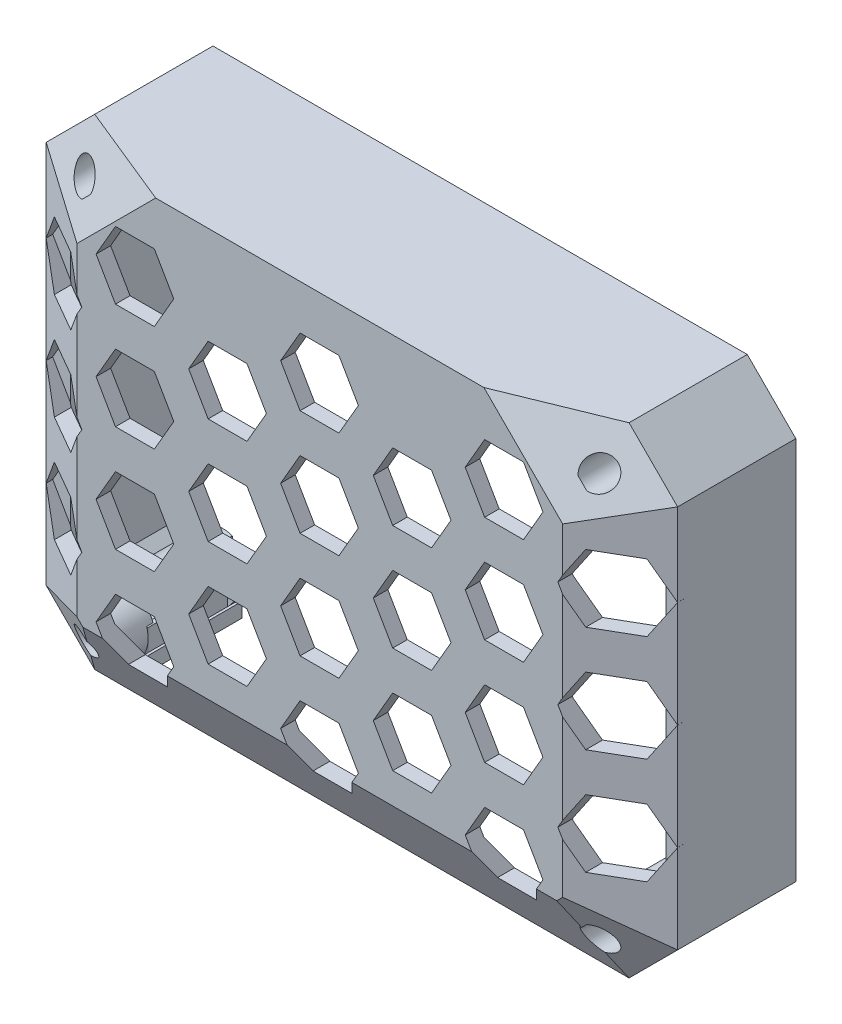
SolidWorks part; units mm, degrees
ref_plane "Front Plane" through (0, 0, 0) normal (0, 0, 1) x (1, 0, 0)
ref_plane "Top Plane" through (0, 0, 0) normal (0, 1, 0) x (1, 0, 0)
ref_plane "Right Plane" through (0, 0, 0) normal (1, 0, 0) x (0, 0, -1)
sketch "Sketch1" plane through (0, 0, 0) normal (0, 0, 1) x (1, 0, 0)
  line L10 (61.5236, 72) -> (30.4764, 72)
  line L11 (20.6915, 72) -> (-9, 72)
  line L12 (-9, 72) -> (-19, 62)
  line L13 (-19, 62) -> (-19, -17)
  line L14 (-19, -17) -> (-9, -27)
  line L15 (-9, -27) -> (101, -27)
  line L16 (101, -27) -> (111, -17)
  line L17 (111, -17) -> (111, 62)
  line L18 (111, 62) -> (101, 72)
  line L19 (101, 72) -> (71.3085, 72)
  line L22 (-9, 72) -> (-19, 62)
  line L23 (-19, 62) -> (-19, -17)
  line L24 (-19, -17) -> (-9, -27)
  line L25 (-9, -27) -> (101, -27)
  line L26 (101, -27) -> (111, -17)
  line L27 (111, -17) -> (111, 62)
  line L28 (111, 62) -> (101, 72)
  line L29 (101, 72) -> (-9, 72)
  arc A2 (61.5236, 72) -> (71.3085, 72) centre (66.4161, 73.0315) ccw
  arc A3 (20.6915, 72) -> (30.4764, 72) centre (25.5839, 73.0315) ccw
  dimension "D1" = 0
extrude "Extrude1" add sketch "Sketch1" along normal blind 33
chamfer "Chamfer1" distance 15 angle 30 8 edges at (-14, -22, 33) (-19, 22.5, 33) (-14, 67, 33) (46, 72, 33) (106, 67, 33) (46, -27, 33) (106, -22, 33) (111, 22.5, 33)
sketch "Sketch2" plane through (0, 0, 0) normal (0, 0, -1) x (-1, 0, 0)
  circle A0 centre (-99, 64) radius 3
  circle A1 centre (7, 64) radius 3
  circle A2 centre (7, -19) radius 3
  circle A3 centre (-99, -19) radius 3
  dimension "D1" = 6
extrude "Cut-Extrude1" cut sketch "Sketch2" against normal blind 30
shell "Shell1" thickness 3
sketch "Sketch3" plane through (0, 0, 33) normal (0, 0, 1) x (1, 0, 0)
  line L0 (3.932, 27.0855) -> (3.932, 19.0855) construction
  line L3 (15.932, 34.0137) -> (11.932, 40.9419)
  line L4 (11.932, 40.9419) -> (3.932, 40.9419)
  line L5 (3.932, 40.9419) -> (-0.068, 34.0137)
  line L6 (-0.068, 34.0137) -> (3.932, 27.0855)
  line L7 (3.932, 27.0855) -> (11.932, 27.0855)
  line L9 (-2.9962, 23.0855) -> (-6.9962, 30.0137)
  line L10 (-6.9962, 30.0137) -> (-14.9962, 30.0137)
  line L11 (-14.9962, 30.0137) -> (-18.9962, 23.0855)
  line L12 (-18.9962, 23.0855) -> (-14.9962, 16.1573)
  line L13 (-14.9962, 16.1573) -> (-6.9962, 16.1573)
  line L14 (-6.9962, 16.1573) -> (-2.9962, 23.0855)
  line L15 (15.932, 12.1573) -> (11.932, 19.0855)
  line L16 (11.932, 19.0855) -> (3.932, 19.0855)
  line L17 (3.932, 19.0855) -> (-0.068, 12.1573)
  line L18 (-0.068, 12.1573) -> (3.932, 5.2291)
  line L19 (3.932, 5.2291) -> (11.932, 5.2291)
  line L20 (11.932, 5.2291) -> (15.932, 12.1573)
  line L21 (11.932, 62.7983) -> (15.932, 55.8701)
  line L22 (-2.9962, 1.2291) -> (-6.9962, 8.1573)
  line L23 (-6.9962, 8.1573) -> (-14.9962, 8.1573)
  line L24 (-14.9962, 8.1573) -> (-18.9962, 1.2291)
  line L25 (-18.9962, 1.2291) -> (-14.9962, -5.6991)
  line L26 (-14.9962, -5.6991) -> (-6.9962, -5.6991)
  line L27 (-6.9962, -5.6991) -> (-2.9962, 1.2291)
  line L28 (15.932, -9.6991) -> (11.932, -2.7709)
  line L29 (11.932, -2.7709) -> (3.932, -2.7709)
  line L30 (3.932, -2.7709) -> (-0.068, -9.6991)
  line L31 (-0.068, -9.6991) -> (3.932, -16.6273)
  line L32 (3.932, -16.6273) -> (11.932, -16.6273)
  line L33 (11.932, -16.6273) -> (15.932, -9.6991)
  line L35 (15.932, 34.0137) -> (11.932, 27.0855)
  line L63 (53.932, 34.0137) -> (49.932, 40.9419)
  line L94 (49.932, 40.9419) -> (41.932, 40.9419)
  line L131 (41.932, 40.9419) -> (37.932, 34.0137)
  line L147 (11.932, 62.7983) -> (3.932, 62.7983)
  line L148 (3.932, 62.7983) -> (-0.068, 55.8701)
  line L149 (-0.068, 55.8701) -> (3.932, 48.9419)
  line L150 (3.932, 48.9419) -> (11.932, 48.9419)
  line L151 (11.932, 48.9419) -> (15.932, 55.8701)
  line L152 (-2.9962, 44.9419) -> (-6.9962, 51.8701)
  line L153 (-6.9962, 51.8701) -> (-14.9962, 51.8701)
  line L154 (-14.9962, 51.8701) -> (-18.9962, 44.9419)
  line L155 (-18.9962, 44.9419) -> (-14.9962, 38.0137)
  line L156 (-14.9962, 38.0137) -> (-6.9962, 38.0137)
  line L157 (-6.9962, 38.0137) -> (-2.9962, 44.9419)
  line L186 (3.932, 48.9419) -> (3.932, 40.9419) construction
  line L242 (37.932, 34.0137) -> (41.932, 27.0855)
  line L243 (41.932, 27.0855) -> (49.932, 27.0855)
  line L244 (35.0038, 23.0855) -> (31.0038, 30.0137)
  line L245 (31.0038, 30.0137) -> (23.0038, 30.0137)
  line L246 (23.0038, 30.0137) -> (19.0038, 23.0855)
  line L247 (19.0038, 23.0855) -> (23.0038, 16.1573)
  line L248 (23.0038, 16.1573) -> (31.0038, 16.1573)
  line L249 (31.0038, 16.1573) -> (35.0038, 23.0855)
  line L250 (53.932, 12.1573) -> (49.932, 19.0855)
  line L262 (49.932, 19.0855) -> (41.932, 19.0855)
  line L263 (41.932, 19.0855) -> (37.932, 12.1573)
  line L279 (37.932, 12.1573) -> (41.932, 5.2291)
  line L299 (17.0432, 35.9383) -> (21.0432, 42.8665) [skipped]
  line L303 (41.932, 5.2291) -> (49.932, 5.2291)
  line L304 (49.932, 5.2291) -> (53.932, 12.1573)
  line L316 (49.932, 62.7983) -> (53.932, 55.8701)
  line L317 (35.0038, 1.2291) -> (31.0038, 8.1573)
  line L318 (31.0038, 8.1573) -> (23.0038, 8.1573)
  line L319 (23.0038, 8.1573) -> (19.0038, 1.2291)
  line L320 (19.0038, 1.2291) -> (23.0038, -5.6991)
  line L321 (23.0038, -5.6991) -> (31.0038, -5.6991)
  line L322 (31.0038, -5.6991) -> (35.0038, 1.2291)
  line L323 (53.932, -9.6991) -> (49.932, -2.7709)
  line L324 (49.932, -2.7709) -> (41.932, -2.7709)
  line L325 (41.932, -2.7709) -> (37.932, -9.6991)
  line L326 (37.932, -9.6991) -> (41.932, -16.6273)
  line L327 (41.932, -16.6273) -> (49.932, -16.6273)
  line L328 (49.932, -16.6273) -> (53.932, -9.6991)
  line L329 (53.932, 34.0137) -> (49.932, 27.0855)
  line L330 (49.932, 62.7983) -> (41.932, 62.7983)
  line L331 (41.932, 62.7983) -> (37.932, 55.8701)
  line L332 (37.932, 55.8701) -> (41.932, 48.9419)
  line L333 (41.932, 48.9419) -> (49.932, 48.9419)
  line L334 (49.932, 48.9419) -> (53.932, 55.8701)
  line L335 (35.0038, 44.9419) -> (31.0038, 51.8701)
  line L336 (31.0038, 51.8701) -> (23.0038, 51.8701)
  line L337 (23.0038, 51.8701) -> (19.0038, 44.9419)
  line L338 (19.0038, 44.9419) -> (23.0038, 38.0137)
  line L339 (23.0038, 38.0137) -> (31.0038, 38.0137)
  line L340 (15.932, 55.8701) -> (11.932, 62.7983) [skipped]
  line L341 (31.0038, 38.0137) -> (35.0038, 44.9419)
  line L342 (41.932, 27.0855) -> (41.932, 19.0855) construction
  line L343 (41.932, 48.9419) -> (41.932, 40.9419) construction
  line L344 (91.932, 34.0137) -> (87.932, 40.9419)
  line L345 (87.932, 40.9419) -> (79.932, 40.9419)
  line L346 (79.932, 40.9419) -> (75.932, 34.0137)
  line L347 (75.932, 34.0137) -> (79.932, 27.0855)
  line L348 (79.932, 27.0855) -> (87.932, 27.0855)
  line L349 (73.0038, 23.0855) -> (69.0038, 30.0137)
  line L350 (69.0038, 30.0137) -> (61.0038, 30.0137)
  line L351 (61.0038, 30.0137) -> (57.0038, 23.0855)
  line L352 (57.0038, 23.0855) -> (61.0038, 16.1573)
  line L353 (61.0038, 16.1573) -> (69.0038, 16.1573)
  line L354 (69.0038, 16.1573) -> (73.0038, 23.0855)
  line L355 (91.932, 12.1573) -> (87.932, 19.0855)
  line L356 (87.932, 19.0855) -> (79.932, 19.0855)
  line L357 (79.932, 19.0855) -> (75.932, 12.1573)
  line L358 (75.932, 12.1573) -> (79.932, 5.2291)
  line L359 (79.932, 5.2291) -> (87.932, 5.2291)
  line L360 (87.932, 5.2291) -> (91.932, 12.1573)
  line L361 (87.932, 62.7983) -> (91.932, 55.8701)
  line L362 (73.0038, 1.2291) -> (69.0038, 8.1573)
  line L363 (69.0038, 8.1573) -> (61.0038, 8.1573)
  line L364 (61.0038, 8.1573) -> (57.0038, 1.2291)
  line L365 (57.0038, 1.2291) -> (61.0038, -5.6991)
  line L366 (61.0038, -5.6991) -> (69.0038, -5.6991)
  line L367 (69.0038, -5.6991) -> (73.0038, 1.2291)
  line L368 (91.932, -9.6991) -> (87.932, -2.7709)
  line L369 (87.932, -2.7709) -> (79.932, -2.7709)
  line L370 (79.932, -2.7709) -> (75.932, -9.6991)
  line L371 (75.932, -9.6991) -> (79.932, -16.6273)
  line L372 (79.932, -16.6273) -> (87.932, -16.6273)
  line L373 (87.932, -16.6273) -> (91.932, -9.6991)
  line L374 (91.932, 34.0137) -> (87.932, 27.0855)
  line L375 (87.932, 62.7983) -> (79.932, 62.7983)
  line L376 (79.932, 62.7983) -> (75.932, 55.8701)
  line L377 (75.932, 55.8701) -> (79.932, 48.9419)
  line L378 (79.932, 48.9419) -> (87.932, 48.9419)
  line L379 (87.932, 48.9419) -> (91.932, 55.8701)
  line L380 (73.0038, 44.9419) -> (69.0038, 51.8701)
  line L381 (69.0038, 51.8701) -> (61.0038, 51.8701)
  line L382 (61.0038, 51.8701) -> (57.0038, 44.9419)
  line L383 (57.0038, 44.9419) -> (61.0038, 38.0137)
  line L384 (61.0038, 38.0137) -> (69.0038, 38.0137)
  line L385 (69.0038, 38.0137) -> (73.0038, 44.9419)
  line L386 (79.932, 27.0855) -> (79.932, 19.0855) construction
  line L387 (79.932, 48.9419) -> (79.932, 40.9419) construction
  line L393 (111.0038, 23.0855) -> (107.0038, 30.0137)
  line L394 (107.0038, 30.0137) -> (99.0038, 30.0137)
  line L395 (99.0038, 30.0137) -> (95.0038, 23.0855)
  line L396 (95.0038, 23.0855) -> (99.0038, 16.1573)
  line L397 (99.0038, 16.1573) -> (107.0038, 16.1573)
  line L398 (107.0038, 16.1573) -> (111.0038, 23.0855)
  line L406 (111.0038, 1.2291) -> (107.0038, 8.1573)
  line L407 (107.0038, 8.1573) -> (99.0038, 8.1573)
  line L408 (99.0038, 8.1573) -> (95.0038, 1.2291)
  line L409 (95.0038, 1.2291) -> (99.0038, -5.6991)
  line L410 (99.0038, -5.6991) -> (107.0038, -5.6991)
  line L411 (107.0038, -5.6991) -> (111.0038, 1.2291)
  line L424 (111.0038, 44.9419) -> (107.0038, 51.8701)
  line L425 (107.0038, 51.8701) -> (99.0038, 51.8701)
  line L426 (99.0038, 51.8701) -> (95.0038, 44.9419)
  line L427 (95.0038, 44.9419) -> (99.0038, 38.0137)
  line L428 (99.0038, 38.0137) -> (107.0038, 38.0137)
  line L429 (107.0038, 38.0137) -> (111.0038, 44.9419)
  line L432 (129.932, 34.0137) -> (125.932, 40.9419) [skipped]
  line L433 (125.932, 40.9419) -> (117.932, 40.9419) [skipped]
  line L434 (117.932, 40.9419) -> (113.932, 34.0137) [skipped]
  line L435 (113.932, 34.0137) -> (117.932, 27.0855) [skipped]
  line L436 (117.932, 27.0855) -> (125.932, 27.0855) [skipped]
  line L437 (129.932, 12.1573) -> (125.932, 19.0855) [skipped]
  line L438 (125.932, 19.0855) -> (117.932, 19.0855) [skipped]
  line L439 (117.932, 19.0855) -> (113.932, 12.1573) [skipped]
  line L440 (113.932, 12.1573) -> (117.932, 5.2291) [skipped]
  line L441 (117.932, 5.2291) -> (125.932, 5.2291) [skipped]
  line L442 (125.932, 5.2291) -> (129.932, 12.1573) [skipped]
  line L443 (125.932, 62.7983) -> (129.932, 55.8701) [skipped]
  line L444 (129.932, -9.6991) -> (125.932, -2.7709) [skipped]
  line L445 (125.932, -2.7709) -> (117.932, -2.7709) [skipped]
  line L446 (117.932, -2.7709) -> (113.932, -9.6991) [skipped]
  line L447 (113.932, -9.6991) -> (117.932, -16.6273) [skipped]
  line L448 (117.932, -16.6273) -> (125.932, -16.6273) [skipped]
  line L449 (125.932, -16.6273) -> (129.932, -9.6991) [skipped]
  line L450 (129.932, 34.0137) -> (125.932, 27.0855) [skipped]
  line L451 (125.932, 62.7983) -> (117.932, 62.7983) [skipped]
  line L452 (117.932, 62.7983) -> (113.932, 55.8701) [skipped]
  line L453 (113.932, 55.8701) -> (117.932, 48.9419) [skipped]
  line L454 (117.932, 48.9419) -> (125.932, 48.9419) [skipped]
  line L455 (125.932, 48.9419) -> (129.932, 55.8701) [skipped]
  line L456 (117.932, 27.0855) -> (117.932, 19.0855) construction
  line L457 (117.932, 48.9419) -> (117.932, 40.9419) construction
  circle A0 centre (27.0038, 23.0855) radius 6.9282 construction
  circle A1 centre (-10.9962, 23.0855) radius 6.9282 construction
  circle A2 centre (27.0038, 1.2291) radius 6.9282 construction
  circle A3 centre (-10.9962, 1.2291) radius 6.9282 construction
  circle A4 centre (27.0038, 44.9419) radius 6.9282 construction
  circle A5 centre (65.0038, 23.0855) radius 6.9282 construction
  circle A6 centre (65.0038, 1.2291) radius 6.9282 construction
  circle A7 centre (65.0038, 44.9419) radius 6.9282 construction
  circle A8 centre (103.0038, 23.0855) radius 6.9282 construction
  circle A9 centre (103.0038, 1.2291) radius 6.9282 construction
  circle A10 centre (103.0038, 44.9419) radius 6.9282 construction
  circle A17 centre (-10.9962, 44.9419) radius 6.9282 construction
  dimension "D2" = 8
  dimension "D3" = 8
  dimension "D4" = 8
  dimension "D5" = 8
  dimension "D6" = 8
  dimension "D7" = 8
  dimension "D8" = 8
  dimension "D9" = 8
  dimension "D11" = 8
  dimension "D12" = 8
  dimension "D15" = 2
extrude "Cut-Extrude2" cut sketch "Sketch3" against normal blind 10
sketch "Sketch5" plane through (0, -27, 0) normal (0, -1, 0) x (1, 0, 0)
  line L0 (101, 24.3397) -> (-9, 24.3397) construction
  line L1 (-1, 21.3397) -> (93, 21.3397)
  line L2 (-3, 19.3397) -> (-3, -14.3155)
  line L3 (-1, -16.3155) -> (93, -16.3155)
  line L4 (95, 19.3397) -> (95, -14.3155)
  line L5 (101, 24.3397) -> (101, 0) construction
  line L6 (-9, 24.3397) -> (-9, 0) construction
  arc A0 (93, 21.3397) -> (95, 19.3397) centre (93, 19.3397) cw
  arc A1 (-3, -14.3155) -> (-1, -16.3155) centre (-1, -14.3155) ccw
  arc A2 (93, -16.3155) -> (95, -14.3155) centre (93, -14.3155) ccw
  arc A3 (-1, 21.3397) -> (-3, 19.3397) centre (-1, 19.3397) ccw
  dimension "D5" = 2
  dimension "D1" = 3
  dimension "D2" = 6
  dimension "D3" = 6
extrude "Cut-Extrude3" cut sketch "Sketch5" against normal blind 10
sketch "Sketch6" plane through (0, 0, 0) normal (0, 0, -1) x (-1, 0, 0)
  circle A0 centre (-99, 64) radius 6
  circle A1 centre (-99, 64) radius 1.6
  circle A2 centre (7, 64) radius 6
  circle A3 centre (7, 64) radius 1.6
  circle A4 centre (7, -19) radius 1.6
  circle A5 centre (7, -19) radius 6
  circle A6 centre (-99, -19) radius 6
  circle A7 centre (-99, -19) radius 1.6
  dimension "D1" = 3.2
extrude "Extrude2" add sketch "Sketch6" against normal blind 3
sketch "Sketch7" plane through (0, 0, 0) normal (0, 0, -1) x (-1, 0, 0)
  line L0 (-96, 61.4) -> (-96, -16.4) construction
  line L1 (-96, 63) -> (4, 63)
  line L2 (-97, 62) -> (-97, -18)
  line L3 (-96, -19) -> (4, -19)
  line L4 (5, 62) -> (5, -18)
  line L5 (3.4, 62) -> (-95.4, 62) construction
  line L6 (4, -16.4) -> (4, 61.4) construction
  line L7 (-95.4, -17) -> (3.4, -17) construction
  arc A0 (4, 63) -> (5, 62) centre (4, 62) cw
  arc A1 (-96, 63) -> (-97, 62) centre (-96, 62) ccw
  arc A2 (4, -19) -> (5, -18) centre (4, -18) ccw
  arc A3 (-97, -18) -> (-96, -19) centre (-96, -18) ccw
  dimension "D5" = 1
  dimension "D1" = 1
  dimension "D2" = 1
  dimension "D3" = 1
  dimension "D4" = 2
extrude "Cut-Extrude4" cut sketch "Sketch7" against normal blind 20
